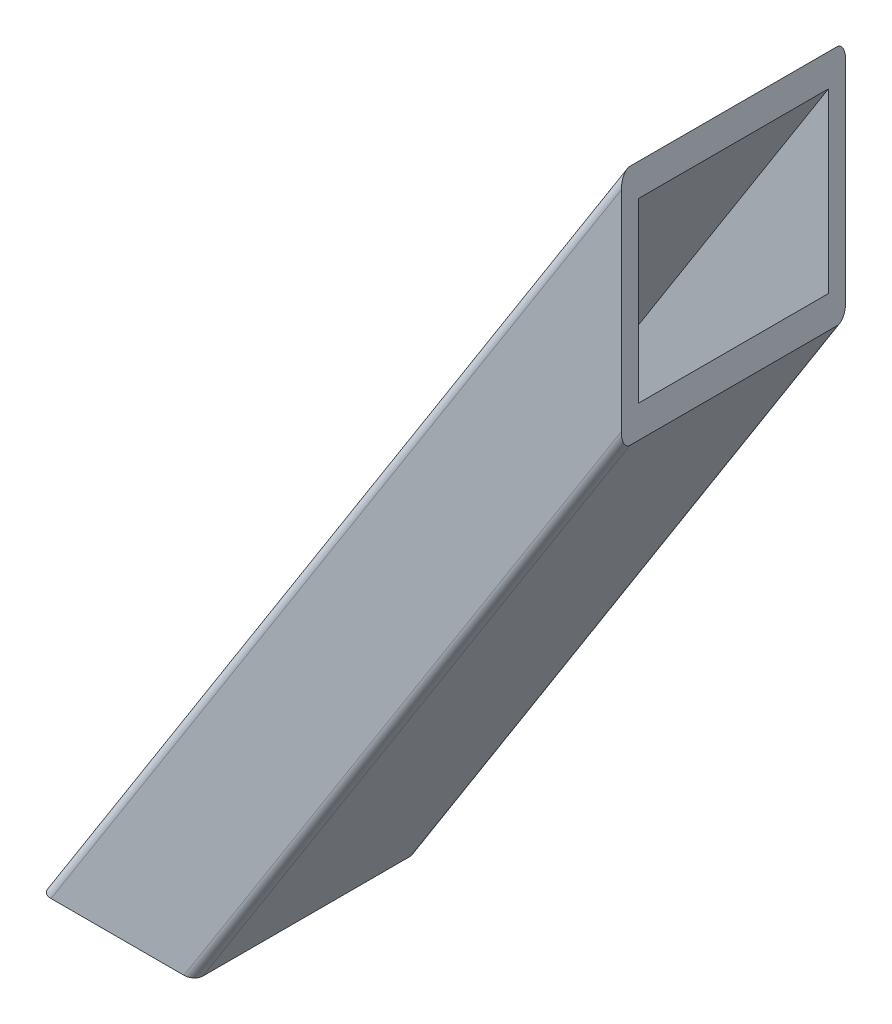
SolidWorks part; units mm, degrees
ref_plane "Front Plane" through (0, 0, 0) normal (0, 0, 1) x (1, 0, 0)
ref_plane "Top Plane" through (0, 0, 0) normal (0, 1, 0) x (1, 0, 0)
ref_plane "Right Plane" through (0, 0, 0) normal (1, 0, 0) x (0, 0, -1)
sketch "Sketch1" plane through (0, 0, 0) normal (0, 0, 1) x (1, 0, 0)
  line L0 (0, 0) -> (-17.7641, 0)
  line L1 (49.4857, 106) -> (49.4857, 78)
  line L2 (0, 0) -> (49.4857, 78)
  line L3 (-17.7641, 0) -> (49.4857, 106)
  line L5 (14.3, 0) -> (-14.3, 0) construction
  dimension "D1" = 106
  dimension "D2" = 15
  dimension "D4" = 28
extrude "Boss-Extrude1" add sketch "Sketch1" along normal blind 26
shell "Shell1" thickness 2
sketch "Sketch2" plane through (0, 2, 0) normal (0, 1, 0) x (1, 0, 0)
  line L0 (-1.0997, -2) -> (-1.0997, -24)
  line L1 (-1.0997, -24) -> (-14.1267, -24)
  line L2 (-14.1267, -24) -> (-14.1267, -2)
  line L3 (-14.1267, -2) -> (-1.0997, -2)
extrude "Cut-Extrude1" cut sketch "Sketch2" against normal up to next
fillet "Fillet1" radius 1 4 edges at (24.7429, 39, 0) (15.8608, 53, 0) (24.7429, 39, 26) (15.8608, 53, 26)
